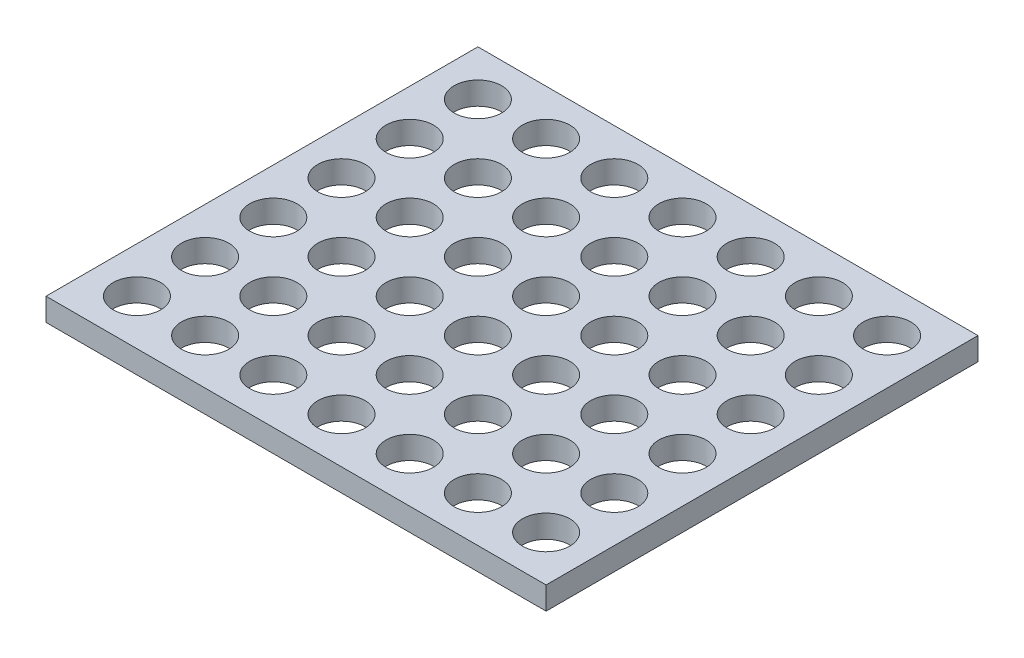
SolidWorks part; units mm, degrees
ref_plane "Front Plane" through (0, 0, 0) normal (0, 0, 1) x (1, 0, 0)
ref_plane "Top Plane" through (0, 0, 0) normal (0, 1, 0) x (1, 0, 0)
ref_plane "Right Plane" through (0, 0, 0) normal (1, 0, 0) x (0, 0, -1)
sketch "Sketch1" plane through (0, 0, 0) normal (0, 1, 0) x (1, 0, 0)
  line L0 (-5.08, 43.18) -> (0, 38.1) construction
  line L1 (-5.08, 43.18) -> (50.8, 43.18)
  line L2 (-5.08, 43.18) -> (-5.08, -5.08)
  line L3 (-5.08, -5.08) -> (50.8, -5.08)
  line L4 (50.8, 43.18) -> (50.8, -5.08)
  line L5 (45.72, 0) -> (50.8, -5.08) construction
  line L6 (45.72, 38.1) -> (50.8, 43.18) construction
  line L7 (0, 0) -> (7.62, 0) construction
  line L8 (0, 0) -> (0, 7.62) construction
  circle A0 centre (0, 0) radius 2.65
  circle A1 centre (7.62, 0) radius 2.65
  circle A2 centre (15.24, 0) radius 2.65
  circle A3 centre (22.86, 0) radius 2.65
  circle A4 centre (30.48, 0) radius 2.65
  circle A5 centre (38.1, 0) radius 2.65
  circle A6 centre (45.72, 0) radius 2.65
  circle A7 centre (7.62, 7.62) radius 2.65
  circle A8 centre (15.24, 7.62) radius 2.65
  circle A9 centre (22.86, 7.62) radius 2.65
  circle A10 centre (30.48, 7.62) radius 2.65
  circle A11 centre (38.1, 7.62) radius 2.65
  circle A12 centre (45.72, 7.62) radius 2.65
  circle A13 centre (7.62, 15.24) radius 2.65
  circle A14 centre (15.24, 15.24) radius 2.65
  circle A15 centre (22.86, 15.24) radius 2.65
  circle A16 centre (30.48, 15.24) radius 2.65
  circle A17 centre (38.1, 15.24) radius 2.65
  circle A18 centre (45.72, 15.24) radius 2.65
  circle A19 centre (7.62, 22.86) radius 2.65
  circle A20 centre (15.24, 22.86) radius 2.65
  circle A21 centre (22.86, 22.86) radius 2.65
  circle A22 centre (30.48, 22.86) radius 2.65
  circle A23 centre (38.1, 22.86) radius 2.65
  circle A24 centre (45.72, 22.86) radius 2.65
  circle A25 centre (7.62, 30.48) radius 2.65
  circle A26 centre (15.24, 30.48) radius 2.65
  circle A27 centre (22.86, 30.48) radius 2.65
  circle A28 centre (30.48, 30.48) radius 2.65
  circle A29 centre (38.1, 30.48) radius 2.65
  circle A30 centre (45.72, 30.48) radius 2.65
  circle A31 centre (7.62, 38.1) radius 2.65
  circle A32 centre (15.24, 38.1) radius 2.65
  circle A33 centre (22.86, 38.1) radius 2.65
  circle A34 centre (30.48, 38.1) radius 2.65
  circle A35 centre (38.1, 38.1) radius 2.65
  circle A36 centre (45.72, 38.1) radius 2.65
  circle A37 centre (0, 7.62) radius 2.65
  circle A38 centre (0, 15.24) radius 2.65
  circle A39 centre (0, 22.86) radius 2.65
  circle A40 centre (0, 30.48) radius 2.65
  circle A41 centre (0, 38.1) radius 2.65
  dimension "D1" = 5.3
  dimension "D4" = 7.62
  dimension "D5" = 7.62
  dimension "D6" = 5.08
  dimension "D7" = 5.08
  dimension "D2" = 7
  dimension "D3" = 6
extrude "Boss-Extrude1" add sketch "Sketch1" along normal blind 2.54
